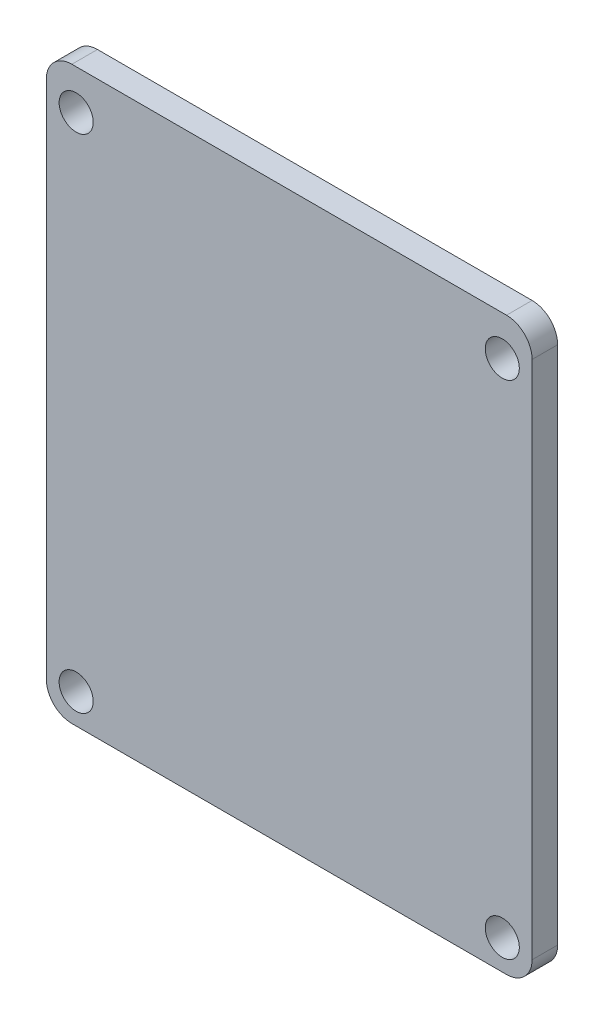
SolidWorks part; units mm, degrees
ref_plane "Přední rovina" through (0, 0, 0) normal (0, 0, 1) x (1, 0, 0)
ref_plane "Horní rovina" through (0, 0, 0) normal (0, 1, 0) x (1, 0, 0)
ref_plane "Pravá rovina" through (0, 0, 0) normal (1, 0, 0) x (0, 0, -1)
sketch "Skica1" plane through (0, 0, 0) normal (0, 0, 1) x (1, 0, 0)
  line L1 (0, 0) -> (57, 0)
  line L2 (0, 0) -> (0, 67)
  line L3 (0, 67) -> (57, 67)
  line L4 (57, 0) -> (57, 67)
  circle A0 centre (3.5, 62.3502) radius 2
  circle A1 centre (53.5, 62.3502) radius 2
  circle A2 centre (53.5, 3.5) radius 2
  circle A3 centre (3.5, 3.5) radius 2
  point P13 (0, 0)
  point P14 (0, 0)
  point P15 (0, 0)
  point P16 (0, 0)
  dimension "D5" = 4
  dimension "D1" = 67
  dimension "D2" = 57
  dimension "D3" = 3.5
  dimension "D4" = 3.5
  dimension "D6" = 50
  dimension "D7" = 58.8502
  dimension "D8" = 3.5
  dimension "D9" = 3.5
  dimension "D10" = 4.6498
extrude "Přidat vysunutím1" add sketch "Skica1" along normal blind 3
sketch "Skica2" plane through (0, 0, 0) normal (0, 0, -1) x (-1, 0, 0)
  text T0 "<r90>L</r>" font "Century Gothic" height 20
  point P1 (-21.641, 28.7979)
  point P2 (0, 0)
  point P3 (0, 0)
extrude "Přidat vysunutím2" add sketch "Skica2" along normal blind 1
fillet "Zaoblit1" radius 3 4 edges at (57, 67, 1.5) (0, 67, 1.5) (0, 0, 1.5) (57, 0, 1.5)
